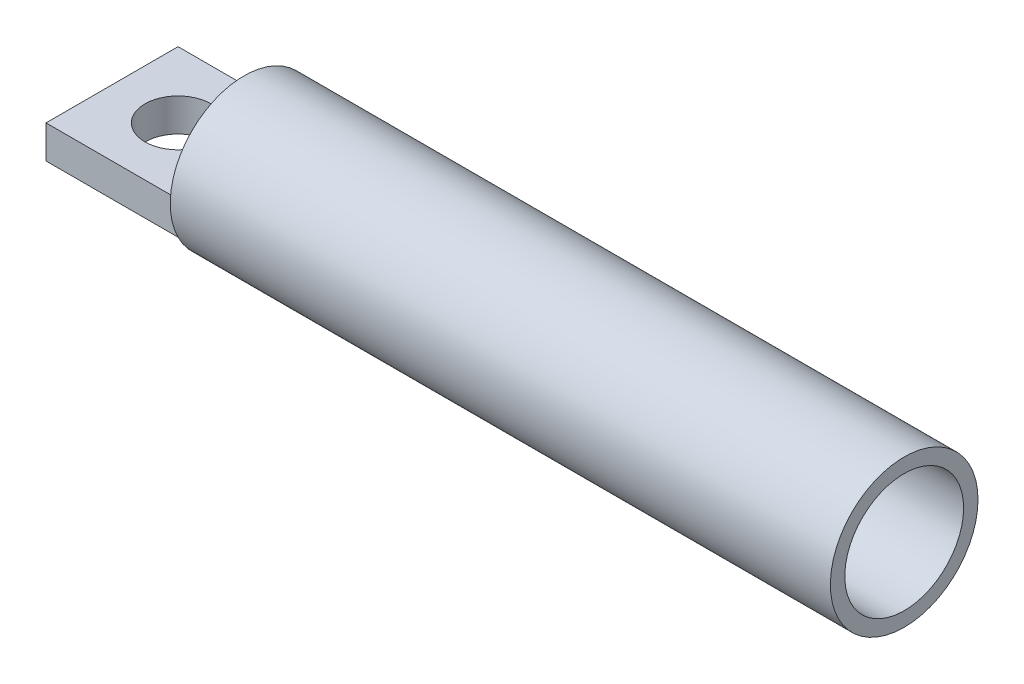
SolidWorks part; units mm, degrees
ref_plane "Front Plane" through (0, 0, 0) normal (0, 0, 1) x (1, 0, 0)
ref_plane "Top Plane" through (0, 0, 0) normal (0, 1, 0) x (1, 0, 0)
ref_plane "Right Plane" through (0, 0, 0) normal (1, 0, 0) x (0, 0, -1)
sketch "Sketch1" plane through (0, 0, 0) normal (0, 1, 0) x (1, 0, 0)
  line L1 (0, 0) -> (50.8, 0)
  line L2 (0, 0) -> (0, 50.8)
  line L3 (0, 50.8) -> (50.8, 50.8)
  line L4 (50.8, 0) -> (50.8, 50.8)
  circle A0 centre (25.4, 25.4) radius 12.7
extrude "Boss-Extrude1" add sketch "Sketch1" along normal blind 12.7
sketch "Sketch2" plane through (50.8, 0, 0) normal (1, 0, 0) x (0, 0, -1)
  line L0 (0, 0) -> (50.8, 12.7) construction
  line L1 (50.8, 12.7) -> (50.8, 0) construction
  line L2 (50.8, 0) -> (25.4, 0) construction
  line L3 (0, 0) -> (50.8, 0) construction
  line L4 (0, 12.7) -> (50.8, 12.7) construction
  circle A0 centre (25.4, 12.7) radius 28.3981
  circle A1 centre (25.4, 12.7) radius 22.86
extrude "Boss-Extrude2" add sketch "Sketch2" along normal blind 254
scale "Scale1" scale about centroid uniform scaling yes scale factor 3
scale "Scale2" scale about centroid uniform scaling yes scale factor 0.333333
scale "Scale3" scale about centroid uniform scaling yes scale factor 2
equation "\"10n\"=8.24"
